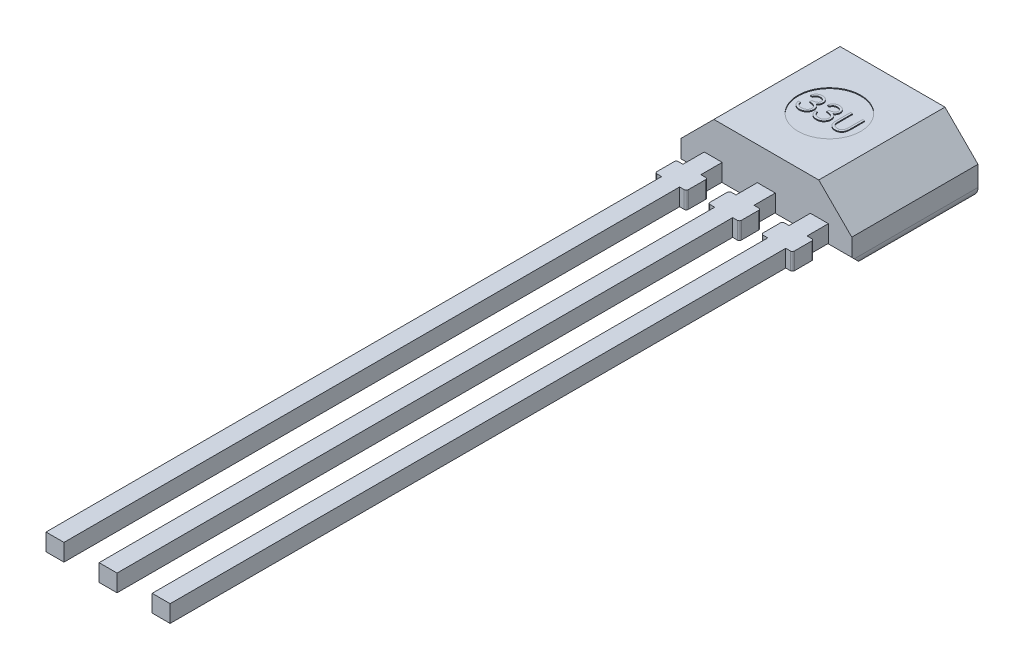
SolidWorks part; units mm, degrees
material "ABS"
ref_plane "Plane1" through (0, 0, 0) normal (0, 0, 1) x (1, 0, 0)
ref_plane "Plane2" through (0, 0, 0) normal (0, 1, 0) x (1, 0, 0)
ref_plane "Plane3" through (0, 0, 0) normal (1, 0, 0) x (0, 0, -1)
sketch "Sketch1" plane through (0, 0, 0) normal (0, 0, 1) x (1, 0, 0)
  line L1 (-2.045, -0.76) -> (2.045, -0.76)
  line L2 (-2.045, -0.76) -> (-2.045, 0.76)
  line L3 (-2.045, 0.76) -> (2.045, 0.76)
  line L4 (2.045, -0.76) -> (2.045, 0.76)
  line L5 (-2.045, -0.76) -> (2.045, 0.76) construction
  line L6 (-2.045, 0.76) -> (2.045, -0.76) construction
  point P0 (0, 0)
  dimension "D1" = 4.09
  dimension "D2" = 1.52
extrude "Boss-Extrude1" add sketch "Sketch1" along normal mid plane 3.02
chamfer "Chamfer1" distance 0.79 angle 45 2 edges at (2.045, 0.76, 0) (-2.045, 0.76, 0)
chamfer "Chamfer2" distance 0.31 angle 45 1 edges at (0, -0.76, 1.51)
sketch "Sketch2" plane through (0, 0, 1.51) normal (0, 0, 1) x (1, 0, 0)
  line L0 (0, -2.7833) -> (0, 2.7833) construction
  line L1 (-1.485, -0.44) -> (-1.055, -0.44)
  line L2 (-1.485, -0.44) -> (-1.485, -0.03)
  line L3 (-1.485, -0.03) -> (-1.055, -0.03)
  line L4 (-1.055, -0.44) -> (-1.055, -0.03)
  line L5 (-1.485, -0.44) -> (-1.055, -0.03) construction
  line L6 (-1.485, -0.03) -> (-1.055, -0.44) construction
  point P0 (-1.27, -0.235)
  dimension "D1" = 0.41
  dimension "D2" = 0.43
  dimension "D3" = 1.27
extrude "Boss-Extrude2" add sketch "Sketch2" along normal blind 15.75
sketch "Sketch3" plane through (-1.055, 0, 0) normal (1, 0, 0) x (0, 0, -1)
  line L0 (-17.26, -0.03) -> (-1.76, -0.03)
  line L1 (-2.26, 0.47) -> (-2.26, 9.6046)
  line L2 (-1.76, 10.1046) -> (2.3906, 10.1046)
  line L4 (-1.51, -0.03) -> (-1.51, 0.76) construction
  line L6 (-2.465, 0.47) -> (-2.465, 9.6046) construction
  line L7 (-1.76, 10.3096) -> (2.3906, 10.3096) construction
  arc A0 (-1.76, -0.03) -> (-2.26, 0.47) centre (-1.76, 0.47) cw
  arc A1 (-2.26, 9.6046) -> (-1.76, 10.1046) centre (-1.76, 9.6046) cw
  arc A2 (-1.76, -0.235) -> (-2.465, 0.47) centre (-1.76, 0.47) cw construction
  arc A3 (-2.465, 9.6046) -> (-1.76, 10.3096) centre (-1.76, 9.6046) cw construction
  dimension "D2" = 0.5
  dimension "D4" = 1.1074
  dimension "D1" = 10.1346
  dimension "D3" = 0.25
  dimension "D6" = 9.1346
  dimension "D8" = 4.1506
  dimension "D5" = 0.205
sketch "Sketch4" plane through (0, 0, 17.26) normal (0, 0, 1) x (1, 0, 0)
  line L4 (-1.055, -0.44) -> (-1.055, -0.03)
  line L5 (-1.055, -0.03) -> (-1.485, -0.03)
  line L6 (-1.485, -0.03) -> (-1.485, -0.44)
  line L7 (-1.485, -0.44) -> (-1.055, -0.44)
  line L8 (-1.055, -0.44) -> (-1.055, -0.03)
  line L9 (-1.055, -0.03) -> (-1.485, -0.03)
  line L10 (-1.485, -0.03) -> (-1.485, -0.44)
  line L11 (-1.485, -0.44) -> (-1.055, -0.44)
  dimension "D1" = 0
sketch "Sketch5" plane through (-1.055, 0, 0) normal (1, 0, 0) x (0, 0, -1)
  line L0 (-17.26, -0.235) -> (-1.2091, -0.235) construction
  line L1 (-17.26, -0.03) -> (-17.26, -0.44) construction
  line L2 (-17.26, -0.03) -> (-1.76, -0.03) construction
  line L3 (-2.26, 0.47) -> (-2.26, 9.6046) construction
  line L4 (-1.76, 10.1046) -> (2.3906, 10.1046) construction
  line L5 (-17.26, -0.03) -> (-1.76, -0.03) construction
  line L6 (-2.26, 0.47) -> (-2.26, 9.6046) construction
  line L7 (-1.76, 10.1046) -> (2.3906, 10.1046) construction
  line L9 (-17.98, -0.94) -> (-17.98, -14.94)
  line L10 (-17.26, -0.44) -> (-17.48, -0.44)
  arc A0 (-2.26, 0.47) -> (-1.76, -0.03) centre (-1.76, 0.47) ccw construction
  arc A1 (-1.76, 10.1046) -> (-2.26, 9.6046) centre (-1.76, 9.6046) ccw construction
  arc A2 (-2.26, 0.47) -> (-1.76, -0.03) centre (-1.76, 0.47) ccw construction
  arc A3 (-1.76, 10.1046) -> (-2.26, 9.6046) centre (-1.76, 9.6046) ccw construction
  arc A5 (-17.98, -0.94) -> (-17.48, -0.44) centre (-17.48, -0.94) cw
  dimension "D1" = 0.5
  dimension "D2" = 0.22
  dimension "D3" = 14
sketch "Sketch6" plane through (0, 0, 17.26) normal (0, 0, 1) x (1, 0, 0)
  line L4 (-1.055, -0.44) -> (-1.055, -0.03)
  line L5 (-1.055, -0.03) -> (-1.485, -0.03)
  line L6 (-1.485, -0.03) -> (-1.485, -0.44)
  line L7 (-1.485, -0.44) -> (-1.055, -0.44)
  line L8 (-1.055, -0.44) -> (-1.055, -0.03)
  line L9 (-1.055, -0.03) -> (-1.485, -0.03)
  line L10 (-1.485, -0.03) -> (-1.485, -0.44)
  line L11 (-1.485, -0.44) -> (-1.055, -0.44)
  dimension "D1" = 0
sweep "Azimuth bend features" [suppressed] add profiles "Sketch6" path "Sketch5"
pattern_linear "LPattern1" count 3 spacing 1.27 along (1, 0, 0) of "Boss-Extrude2", "Azimuth bend features"
sketch "Sketch15" [suppressed] plane through (0, 0, 0) normal (1, 0, 0) x (0, 0, -1)
  line L1 (-2.399, -0.44) -> (-1.76, -0.44)
  line L2 (-2.399, -0.44) -> (-2.399, -0.03)
  line L3 (-2.399, -0.03) -> (-1.76, -0.03)
  line L4 (-1.76, -0.44) -> (-1.76, -0.03)
extrude "Cut-Extrude4" [suppressed] cut sketch "Sketch15" against normal through all both and the other way through all
sketch "Sketch16" [suppressed] plane through (-1.055, 0, 0) normal (1, 0, 0) x (0, 0, -1)
  line L0 (-1.76, -0.235) -> (-2.8251, -0.235) construction
  line L1 (-2.26, 0.47) -> (-2.26, 9.6046) construction
  line L2 (-1.76, 10.1046) -> (2.3906, 10.1046) construction
  line L3 (-1.76, 10.1046) -> (2.3906, 10.1046) construction
  line L4 (-2.26, 0.47) -> (-2.26, 9.6046) construction
  line L5 (-1.76, -10.5746) -> (2.3906, -10.5746)
  line L6 (-2.26, -0.94) -> (-2.26, -10.0746)
  arc A0 (-2.26, 0.47) -> (-1.76, -0.03) centre (-1.76, 0.47) ccw construction
  arc A1 (-1.76, 10.1046) -> (-2.26, 9.6046) centre (-1.76, 9.6046) ccw construction
  arc A2 (-1.76, 10.1046) -> (-2.26, 9.6046) centre (-1.76, 9.6046) ccw construction
  arc A3 (-2.26, 0.47) -> (-1.76, -0.03) centre (-1.76, 0.47) ccw construction
  arc A4 (-1.76, -10.5746) -> (-2.26, -10.0746) centre (-1.76, -10.0746) cw
  arc A5 (-2.26, -0.94) -> (-1.76, -0.44) centre (-1.76, -0.94) cw
sketch "Sketch17" [suppressed] plane through (0, 0, 1.76) normal (0, 0, 1) x (1, 0, 0)
  line L4 (-1.055, -0.03) -> (-1.485, -0.03)
  line L5 (-1.485, -0.03) -> (-1.485, -0.44)
  line L6 (-1.485, -0.44) -> (-1.055, -0.44)
  line L7 (-1.055, -0.44) -> (-1.055, -0.03)
  line L8 (-1.055, -0.03) -> (-1.485, -0.03)
  line L9 (-1.485, -0.03) -> (-1.485, -0.44)
  line L10 (-1.485, -0.44) -> (-1.055, -0.44)
  line L11 (-1.055, -0.44) -> (-1.055, -0.03)
  dimension "D1" = 0
sweep "Sweep5" [suppressed] add profiles "Sketch17" path "Sketch16"
pattern_linear "LPattern4" [suppressed] count 3 spacing 1.27
sketch "Sketch11" [suppressed] plane through (0, 0, 0) normal (1, 0, 0) x (0, 0, -1)
  line L1 (-2.399, -0.44) -> (-1.76, -0.44)
  line L2 (-2.399, -0.44) -> (-2.399, -0.03)
  line L3 (-2.399, -0.03) -> (-1.76, -0.03)
  line L4 (-1.76, -0.44) -> (-1.76, -0.03)
extrude "Cut-Extrude2" [suppressed] cut sketch "Sketch11" against normal through all both and the other way through all
sketch "Sketch13" [suppressed] plane through (-1.055, 0, 0) normal (1, 0, 0) x (0, 0, -1)
  line L0 (-2.26, 0.47) -> (-2.26, 9.6046) construction
  line L1 (-1.76, 10.1046) -> (2.3906, 10.1046) construction
  line L2 (-2.26, 0.47) -> (-2.26, 9.6046)
  line L3 (-1.76, 10.1046) -> (2.3906, 10.1046)
  arc A0 (-2.26, 0.47) -> (-1.76, -0.03) centre (-1.76, 0.47) ccw construction
  arc A1 (-1.76, 10.1046) -> (-2.26, 9.6046) centre (-1.76, 9.6046) ccw construction
  arc A2 (-2.26, 0.47) -> (-1.76, -0.03) centre (-1.76, 0.47) ccw
  arc A3 (-1.76, 10.1046) -> (-2.26, 9.6046) centre (-1.76, 9.6046) ccw
sketch "Sketch12" [suppressed] plane through (0, 0, 1.76) normal (0, 0, 1) x (1, 0, 0)
  line L4 (-1.055, -0.03) -> (-1.485, -0.03)
  line L5 (-1.485, -0.03) -> (-1.485, -0.44)
  line L6 (-1.485, -0.44) -> (-1.055, -0.44)
  line L7 (-1.055, -0.44) -> (-1.055, -0.03)
  line L8 (-1.055, -0.03) -> (-1.485, -0.03)
  line L9 (-1.485, -0.03) -> (-1.485, -0.44)
  line L10 (-1.485, -0.44) -> (-1.055, -0.44)
  line L11 (-1.055, -0.44) -> (-1.055, -0.03)
  dimension "D1" = 0
sweep "Sweep4" [suppressed] add profiles "Sketch12" path "Sketch13"
pattern_linear "LPattern3" [suppressed] count 3 spacing 1.27
sketch "Sketch18" plane through (0, 0.76, 0) normal (0, 1, 0) x (1, 0, 0)
  circle A0 centre (0, 0) radius 0.75
  dimension "D1" = 1.5
extrude "Cut-Extrude5" cut sketch "Sketch18" against normal blind 0.02
sketch "Sketch19" plane through (0, 0.74, 0) normal (0, 1, 0) x (1, 0, 0)
  line L0 (-0.7028, -0.2618) -> (0.7028, -0.2618) construction
  circle A0 centre (0, 0) radius 0.75 construction
  text T0 "33U" font "Century Gothic" height in points 2
extrude "Boss-Extrude3" add sketch "Sketch19" along normal blind 0.02
fillet "Fillet1" radius 0.25 2 edges at (2.045, -0.76, -0.155) (-2.045, -0.76, -0.155)
sketch "Sketch20" plane through (0, -0.03, 0) normal (0, 1, 0) x (1, 0, 0)
  line L0 (-1.27, -1.51) -> (-1.27, -2.275) construction
  line L1 (-1.055, -1.51) -> (-1.485, -1.51) construction
  line L3 (-1.645, -2.02) -> (-0.895, -2.02)
  line L4 (-1.645, -2.02) -> (-1.645, -2.53)
  line L5 (-1.645, -2.53) -> (-0.895, -2.53)
  line L6 (-0.895, -2.02) -> (-0.895, -2.53)
  line L7 (-1.645, -2.02) -> (-0.895, -2.53) construction
  line L8 (-1.645, -2.53) -> (-0.895, -2.02) construction
  dimension "D1" = 1.02
  dimension "D2" = 0.51
  dimension "D3" = 0.75
extrude "DANBAR REMOVAL PROTRUSION" add sketch "Sketch20" against normal up to surface (0.41 mm away) up to face at (-1.27, -0.44, 9.385)
fillet "Fillet2" radius 0.05 4 edges at (-0.895, -0.235, 2.02) (-0.895, -0.235, 2.53) (-1.645, -0.235, 2.02) (-1.645, -0.235, 2.53)
pattern_linear "LPattern5" count 3 spacing 1.27 along (1, 0, 0) of "DANBAR REMOVAL PROTRUSION", "Fillet2"
equation "\"D3@LPattern3\"=\"D3@LPattern1\""
equation "\"D3@LPattern4\"=\"D3@LPattern1\""
